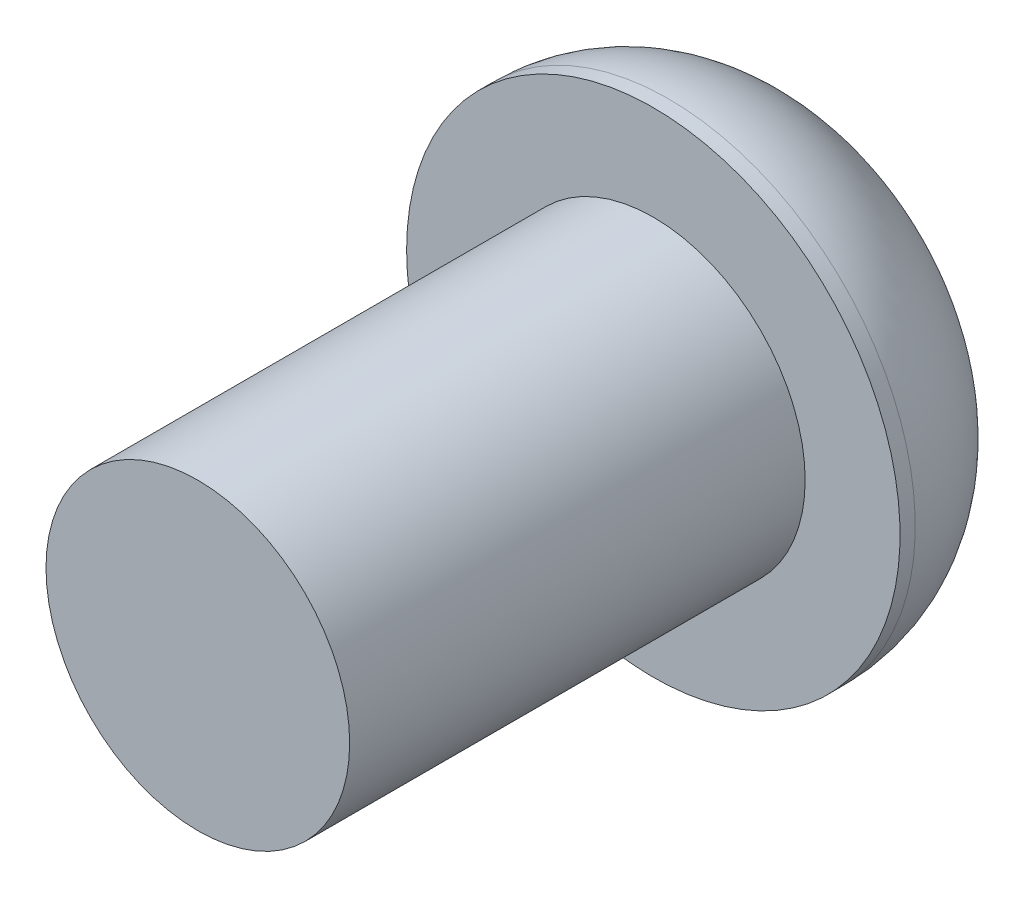
SolidWorks part; units mm, degrees
ref_plane "前视基准面" through (0, 0, 0) normal (0, 0, 1) x (1, 0, 0)
ref_plane "上视基准面" through (0, 0, 0) normal (0, 1, 0) x (1, 0, 0)
ref_plane "右视基准面" through (0, 0, 0) normal (1, 0, 0) x (0, 0, -1)
sketch "草图1" plane through (0, 0, 0) normal (0, 0, 1) x (1, 0, 0)
  circle A0 centre (0, 0) radius 2
  dimension "D1" = 4
extrude "凸台-拉伸1" add sketch "草图1" along normal blind 6
sketch "草图2" plane through (0, 0, 0) normal (0, 0, -1) x (-1, 0, 0)
  circle A0 centre (0, 0) radius 3.25
  dimension "D1" = 6.5
extrude "凸台-拉伸2" add sketch "草图2" along normal blind 2.2
fillet "圆角1" radius 2 1 edges at (-3.25, 0, -2.2)
sketch "草图3" plane through (0, 0, -2.2) normal (0, 0, -1) x (-1, 0, 0)
  line L0 (0, 3.24) -> (0, -3.24) construction
  line L1 (-3.24, 0) -> (3.24, 0) construction
  line L2 (-3.24, 0.25) -> (3.24, 0.25) construction
  line L3 (0.25, 3.24) -> (0.25, -3.24) construction
  line L4 (-3.24, -0.25) -> (3.24, -0.25) construction
  line L5 (-0.25, 3.24) -> (-0.25, -3.24) construction
  line L7 (3.24, 0.25) -> (3.24, -0.25)
  line L8 (-0.25, 3.24) -> (0.25, 3.24)
  line L10 (-0.25, 3.24) -> (-0.25, 0.25)
  line L11 (0.25, 3.24) -> (0.25, 0.25)
  line L12 (3.24, 0.25) -> (0.25, 0.25)
  line L13 (3.24, -0.25) -> (0.25, -0.25)
  line L15 (0.25, -3.24) -> (0.25, -0.25)
  line L16 (-0.25, -3.24) -> (-0.25, -0.25)
  line L17 (0.25, -3.24) -> (-0.25, -3.24)
  line L18 (-3.24, -0.25) -> (-0.25, -0.25)
  line L19 (-3.24, 0.25) -> (-0.25, 0.25)
  line L20 (-3.24, -0.25) -> (-3.24, 0.25)
  line L21 (3.24, 0.25) -> (3.24, -0.25) [skipped]
  circle A1 centre (0, 0) radius 3.24 construction
  dimension "D1" = 0.25
  dimension "D2" = 0.25
  dimension "D3" = 4
extrude "切除-拉伸1" cut sketch "草图3" against normal blind 0.5
